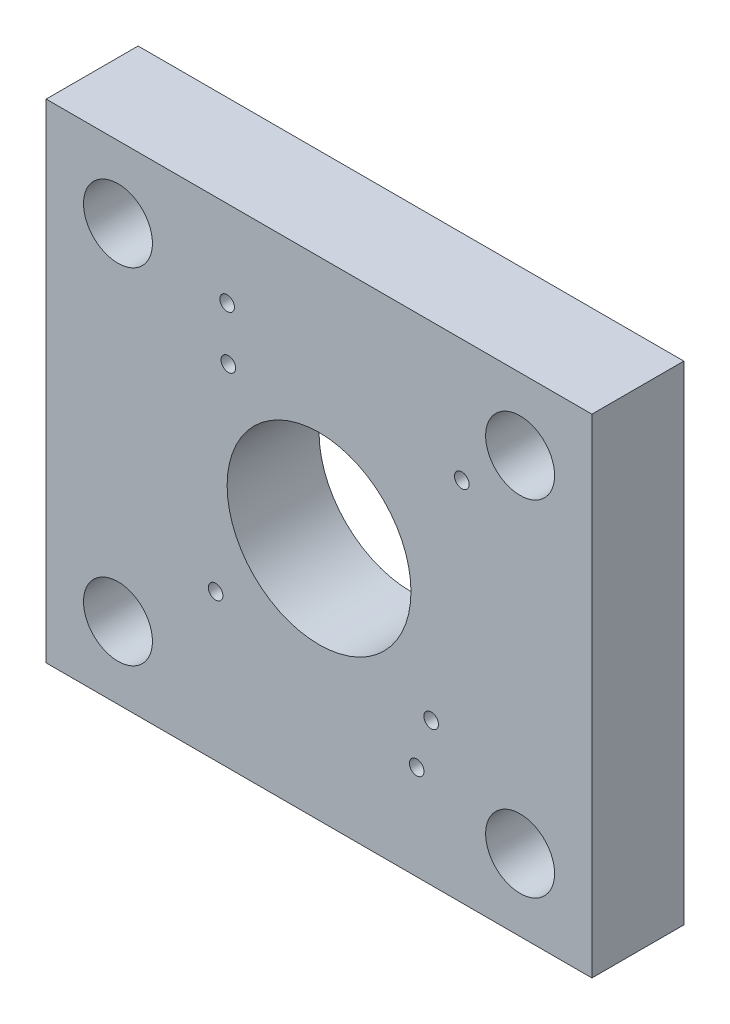
SolidWorks part; units mm, degrees
ref_plane "Front Plane" through (0, 0, 0) normal (0, 0, 1) x (1, 0, 0)
ref_plane "Top Plane" through (0, 0, 0) normal (0, 1, 0) x (1, 0, 0)
ref_plane "Right Plane" through (0, 0, 0) normal (1, 0, 0) x (0, 0, -1)
ref_plane "Dielectric_Layer Layer 1" through (0, 0, 1.6) normal (0, 0, 1) x (1, 0, 0)
sketch "Sketch1" plane through (0, 0, 0) normal (0, 0, 1) x (1, 0, 0)
  line L0 (-0.25, 8.25) -> (9.25, 8.25)
  line L1 (9.25, 8.25) -> (9.25, -0.25)
  line L2 (9.25, -0.25) -> (-0.25, -0.25)
  line L3 (-0.25, -0.25) -> (-0.25, 8.25)
extrude "Board_Outline" add sketch "Sketch1" along normal blind 1.6 separate body
sketch "Sketch2" plane through (0, 0, 0) normal (0, 0, 1) x (1, 0, 0)
  circle A0 centre (8, 7) radius 0.6
  circle A1 centre (1, 7) radius 0.6
  circle A2 centre (1, 1) radius 0.6
  circle A3 centre (8, 1) radius 0.6
  circle A4 centre (4.5, 4) radius 1.6
  circle A5 centre (2.7, 2.3) radius 0.127
  circle A6 centre (6.2, 1.4) radius 0.127
  circle A7 centre (2.9, 6.7492) radius 0.127
  circle A8 centre (2.921, 5.842) radius 0.127
  circle A9 centre (6.4516, 2.2352) radius 0.127
  circle A10 centre (6.985, 6.1214) radius 0.127
extrude "NPTH" cut sketch "Sketch2" along normal through all
ref_plane "Plane1" through (4.5, 0, 0) normal (1, 0, 0) x (0, 0, -1)
ref_plane "Plane2" through (0, 4, 0) normal (0, 1, 0) x (1, 0, 0)
